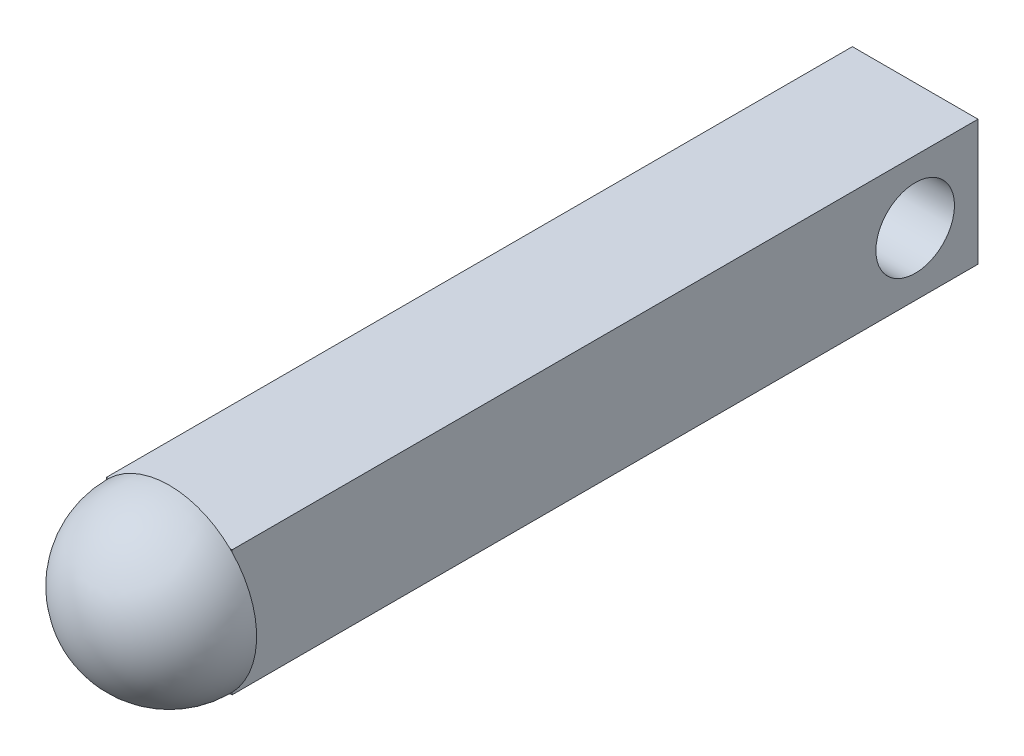
SolidWorks part; units mm, degrees
ref_plane "Front Plane" through (0, 0, 0) normal (0, 0, 1) x (1, 0, 0)
ref_plane "Top Plane" through (0, 0, 0) normal (0, 1, 0) x (1, 0, 0)
ref_plane "Right Plane" through (0, 0, 0) normal (1, 0, 0) x (0, 0, -1)
sketch "Sketch1" plane through (0, 0, 0) normal (0, 0, 1) x (1, 0, 0)
  line L1 (-8, -8) -> (8, -8)
  line L2 (-8, -8) -> (-8, 8)
  line L3 (-8, 8) -> (8, 8)
  line L4 (8, -8) -> (8, 8)
  line L5 (-8, -8) -> (8, 8) construction
  line L6 (-8, 8) -> (8, -8) construction
  point P0 (0, 0)
  dimension "D1" = 16
  dimension "D2" = 16
extrude "Boss-Extrude1" add sketch "Sketch1" along normal blind 95
sketch "Sketch2" plane through (-8, 0, 0) normal (-1, 0, 0) x (0, 0, 1)
  line L0 (0, 0) -> (95, 0) construction
  line L1 (95, 8) -> (95, -8) construction
  line L2 (0, 8) -> (0, -8) construction
  circle A0 centre (8, 0) radius 5
  dimension "D1" = 10
  dimension "D2" = 8
extrude "Cut-Extrude1" cut sketch "Sketch2" against normal blind 75
sketch "Sketch3" plane through (0, 0, 0) normal (1, 0, 0) x (0, 0, -1)
  line L0 (-95, 8) -> (-95, -8) construction
  line L1 (-95, 11.1252) -> (-95, 0)
  line L2 (-95, 0) -> (-106.1252, 0)
  arc A0 (-95, 11.1252) -> (-106.1252, 0) centre (-95, 0) ccw
revolve "Revolve1" add sketch "Sketch3" angle 360 about L2
